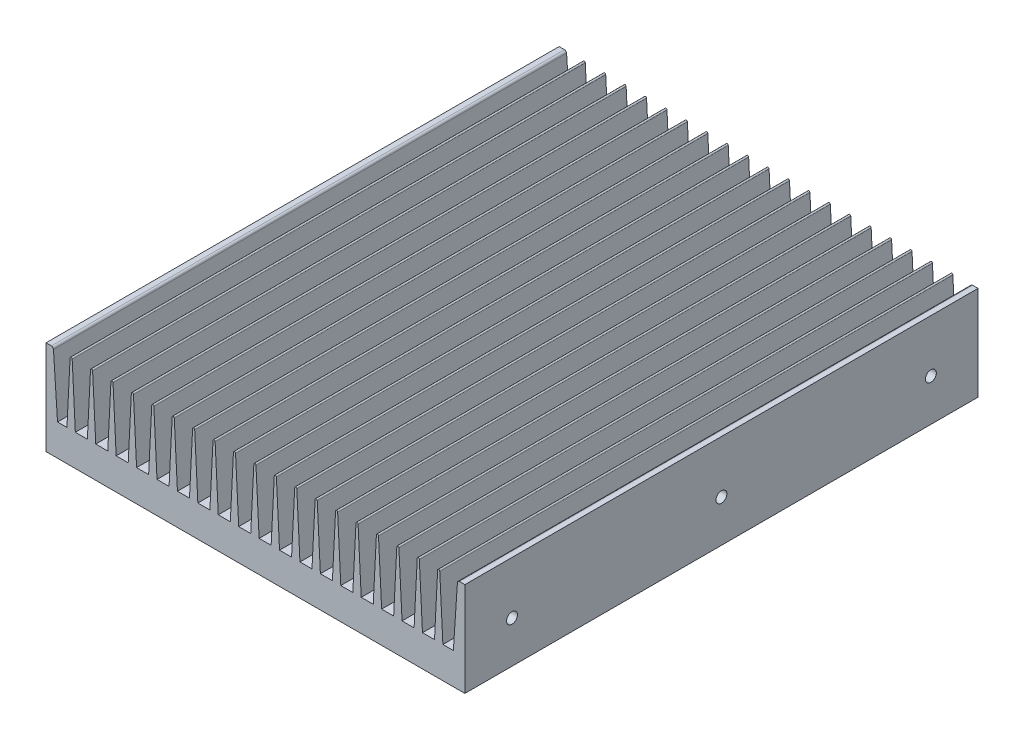
SolidWorks part; units mm, degrees
ref_plane "Спереди" through (0, 0, 0) normal (0, 0, 1) x (1, 0, 0)
ref_plane "Сверху" through (0, 0, 0) normal (0, 1, 0) x (1, 0, 0)
ref_plane "Справа" through (0, 0, 0) normal (1, 0, 0) x (0, 0, -1)
sketch "Эскиз1" plane through (0, 0, 0) normal (0, 0, 1) x (1, 0, 0)
  line L0 (0, 45) -> (2.5644, 45)
  line L1 (0, 0) -> (200, 0)
  line L2 (3.5622, 44.0665) -> (5.5, 15)
  line L3 (0, 45) -> (0, 0)
  line L4 (200, 45) -> (200, 0)
  line L5 (100, 63.7127) -> (100, -22.2582) construction
  line L8 (200, 45) -> (197.4356, 45)
  line L9 (196.4378, 44.0665) -> (194.5, 15)
  line L10 (5.5, 15) -> (194.5, 15)
  arc A0 (2.5644, 45) -> (3.5622, 44.0665) centre (2.5644, 44) cw
  arc A2 (197.4356, 45) -> (196.4378, 44.0665) centre (197.4356, 44) ccw
  point P18 (196.5, 45)
  dimension "D9" = 1
  dimension "D1" = 200
  dimension "D2" = 15
  dimension "D3" = 45
  dimension "D4" = 5.5
  dimension "D7" = 3.5
extrude "Вытянуть1" add sketch "Эскиз1" along normal blind 245
sketch "Эскиз2" plane through (0, 0, 245) normal (0, 0, 1) x (1, 0, 0)
  line L0 (194.5, 15) -> (5.5, 15) construction
  line L1 (11.5, 44.5) -> (10, 15)
  line L2 (12, 44.5) -> (12, 22.5548) construction
  line L3 (12.5, 44.5) -> (14, 15)
  line L4 (10, 15) -> (14, 15)
  line L6 (0, 45) -> (0, 0) construction
  arc A0 (11.5, 44.5) -> (12.5, 44.5) centre (12, 44.5) cw
  dimension "D1" = 30
  dimension "D3" = 0.5
  dimension "D2" = 4
  dimension "D4" = 12
  dimension "D5" = 1
extrude "Вытянуть3" add sketch "Эскиз2" against normal blind 245
pattern_curve "Кривая1" of "Вытянуть3" along edge at (100, 0, 0) parameters "D1"=19, "D3"=9.75, "D2"=1, "D4"=50
sketch "Эскиз6" plane through (0, 0, 0) normal (0, 0, -1) x (-1, 0, 0)
  line L0 (0, 0) -> (-200, 0) construction
  line L1 (0, 45) -> (0, 0) construction
  line L2 (-200, 0) -> (-200, 45) construction
  circle A0 centre (-4, 6) radius 2.5
  circle A1 centre (-196, 6) radius 2.5
  dimension "D1" = 5
  dimension "D2" = 6
  dimension "D3" = 4
  dimension "D4" = 6
  dimension "D6" = 5
  dimension "D5" = 4
extrude "Вырез-Вытянуть3" cut sketch "Эскиз6" against normal blind 8
sketch "Эскиз7" plane through (0, 0, 0) normal (-1, 0, 0) x (0, 0, 1)
  line L0 (-24.1676, 20) -> (275.3481, 20) construction
  line L1 (122.5, 109.9776) -> (122.5, -31.6981) construction
  line L2 (245, 45) -> (245, 0) construction
  line L3 (0, 45) -> (0, 0) construction
  line L4 (245, 0) -> (0, 0) construction
  circle A0 centre (22.5, 20) radius 2.6
  circle A1 centre (222.5, 20) radius 2.6
  circle A2 centre (122.5, 20) radius 2.6
  dimension "D2" = 5.2
  dimension "D3" = 200
  dimension "D1" = 20
extrude "Вырез-Вытянуть4" cut sketch "Эскиз7" against normal blind 6
sketch "Эскиз8" plane through (200, 0, 0) normal (1, 0, 0) x (0, 0, -1)
  line L0 (9.57, 30) -> (-255.3048, 30) construction
  line L1 (-245, 45) -> (0, 45) construction
  line L2 (-122.5, 20) -> (-122.5, -38.851) construction
  line L3 (0, 0) -> (0, 45) construction
  line L4 (-245, 0) -> (-245, 45) construction
  circle A0 centre (-80, 30) radius 4.5
  circle A1 centre (-165, 30) radius 3.4
  dimension "D2" = 9
  dimension "D3" = 6.8
  dimension "D5" = 80
  dimension "D1" = 15
  dimension "D4" = 80
extrude "Вырез-Вытянуть5" cut sketch "Эскиз8" against normal blind 6
sketch "Эскиз9" plane through (200, 0, 0) normal (1, 0, 0) x (0, 0, -1)
  circle A0 centre (-22.5, 20) radius 2.6 construction
  circle A1 centre (-22.5, 20) radius 2.6
  circle A2 centre (-122.5, 20) radius 2.6 construction
  circle A3 centre (-122.5, 20) radius 2.6
  circle A4 centre (-222.5, 20) radius 2.6 construction
  circle A5 centre (-222.5, 20) radius 2.6
extrude "Вырез-Вытянуть6" cut sketch "Эскиз9" against normal blind 6
cosmetic thread "Условное изображение резьбы9" parameters "D1"=4.34, "D2"=6
cosmetic thread "Условное изображение резьбы10" parameters "D1"=4.34, "D2"=6
cosmetic thread "Условное изображение резьбы11" parameters "D1"=4.34, "D2"=6
cosmetic thread "Условное изображение резьбы35"
cosmetic thread "Условное изображение резьбы36"
cosmetic thread "Условное изображение резьбы37"
sketch "Эскиз11" plane through (0, 0, 0) normal (-1, 0, 0) x (0, 0, 1)
  circle A0 centre (22.5, 20) radius 2.6 construction
  circle A1 centre (22.5, 20) radius 2.6
  circle A2 centre (122.5, 20) radius 2.6 construction
  circle A3 centre (122.5, 20) radius 2.6
  circle A4 centre (222.5, 20) radius 2.6 construction
  circle A5 centre (222.5, 20) radius 2.6
extrude "Вытянуть4" add sketch "Эскиз11" against normal up to surface (5.34 mm away)
sketch "Эскиз12" plane through (200, 0, 0) normal (1, 0, 0) x (0, 0, -1)
  circle A0 centre (-80, 30) radius 4.5 construction
  circle A1 centre (-80, 30) radius 4.5
  circle A2 centre (-165, 30) radius 3.4 construction
  circle A3 centre (-165, 30) radius 3.4
extrude "Вытянуть5" add sketch "Эскиз12" against normal up to surface (4.5 mm away)
sketch "Эскиз19" plane through (0, 0, 0) normal (-1, 0, 0) x (0, 0, 1)
  circle A0 centre (222.5, 20) radius 2.6 construction
  circle A1 centre (222.5, 20) radius 2.6
  circle A2 centre (122.5, 20) radius 2.6 construction
  circle A3 centre (122.5, 20) radius 2.6
  circle A4 centre (22.5, 20) radius 2.6 construction
  circle A5 centre (22.5, 20) radius 2.6
extrude "Вырез-Вытянуть12" cut sketch "Эскиз19" against normal blind 8
cosmetic thread "Условное изображение резьбы32"
cosmetic thread "Условное изображение резьбы33"
cosmetic thread "Условное изображение резьбы34"
sketch "Эскиз21" plane through (0, 0, 0) normal (0, -1, 0) x (1, 0, 0)
  line L2 (45, 165) -> (45, 15) construction
  line L3 (45, 165) -> (155, 165) construction
  line L4 (155, 165) -> (155, 15) construction
  line L5 (155, 15) -> (45, 15) construction
  line L6 (78, 74.5) -> (118.3996, 74.5) construction
  line L7 (78, 74.5) -> (78, 142.8649) construction
  line L8 (123, 74.5) -> (123, 13.7412) construction
  line L9 (78, 45) -> (107.3234, 45) construction
  line L10 (45, 15) -> (155, 15) construction
  line L11 (98, 233.0587) -> (98, 162.2382) construction
  line L12 (0, 245) -> (0, 0) construction
  line L14 (0, 245) -> (200, 245) construction
  circle A0 centre (118, 96.5) radius 2.6
  circle A1 centre (45, 165) radius 1.6
  circle A2 centre (45, 15) radius 1.6
  circle A3 centre (155, 15) radius 1.6
  circle A4 centre (155, 165) radius 1.6
  circle A5 centre (78, 74.5) radius 1.3
  circle A6 centre (123, 74.5) radius 1.3
  circle A7 centre (78, 45) radius 1.3
  circle A8 centre (123, 45) radius 1.3
  circle A9 centre (122.5, 129.25) radius 1.3
  circle A10 centre (98, 235) radius 2.1
  circle A11 centre (145, 100) radius 2.1
  circle A12 centre (98, 180) radius 2.1
  dimension "D8" = 37
  dimension "D11" = 33
  dimension "D12" = 30
  dimension "D10" = 4.2
  dimension "D13" = 85
  dimension "D15" = 32.5
  dimension "D17" = 5.2
  dimension "D18" = 10
  dimension "D20" = 15
  dimension "D28" = 3.2
  dimension "D9" = 81.5
  dimension "D14" = 10
  dimension "D16" = 114.25
  dimension "D19" = 55
  dimension "D3" = 45
  dimension "D21" = 4.2
  dimension "D4" = 110
  dimension "D5" = 150
  dimension "D6" = 45
  dimension "D7" = 29.5
extrude "Вырез-Вытянуть13" cut sketch "Эскиз21" against normal blind 10
cosmetic thread "Условное изображение резьбы38" parameters "D1"=10, "D2"=4
cosmetic thread "Условное изображение резьбы39" parameters "D1"=10, "D2"=4
cosmetic thread "Условное изображение резьбы40" parameters "D1"=10, "D2"=4
cosmetic thread "Условное изображение резьбы41" parameters "D1"=10, "D2"=4
cosmetic thread "Условное изображение резьбы42" parameters "D1"=8, "D2"=3
cosmetic thread "Условное изображение резьбы43" parameters "D1"=8, "D2"=3
cosmetic thread "Условное изображение резьбы44" parameters "D1"=8, "D2"=3
cosmetic thread "Условное изображение резьбы45" parameters "D1"=8, "D2"=3
cosmetic thread "Условное изображение резьбы46" parameters "D1"=8, "D2"=3
cosmetic thread "Условное изображение резьбы47" parameters "D1"=8, "D2"=5
cosmetic thread "Условное изображение резьбы48" parameters "D2"=5
cosmetic thread "Условное изображение резьбы49" parameters "D2"=5
